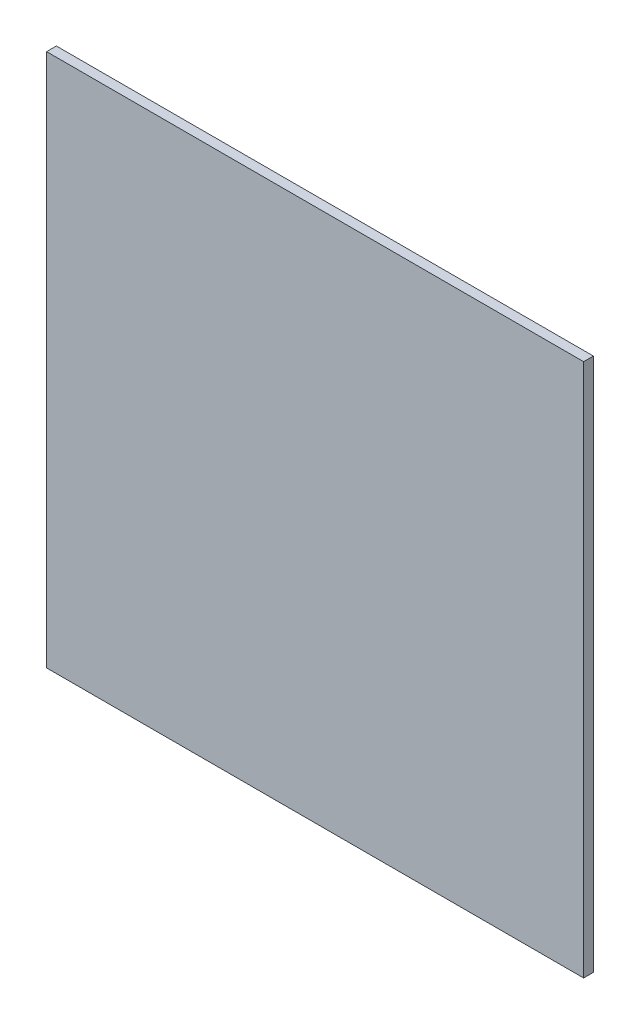
SolidWorks part; units mm, degrees
ref_plane "Plan de face" through (0, 0, 0) normal (0, 0, 1) x (1, 0, 0)
ref_plane "Plan de dessus" through (0, 0, 0) normal (0, 1, 0) x (1, 0, 0)
ref_plane "Plan de droite" through (0, 0, 0) normal (1, 0, 0) x (0, 0, -1)
sketch "Esquisse1" plane through (0, 0, 0) normal (0, 0, 1) x (1, 0, 0)
  line L1 (0, 0) -> (-330, 0)
  line L2 (0, 0) -> (0, 328)
  line L3 (0, 328) -> (-330, 328)
  line L4 (-330, 0) -> (-330, 328)
  dimension "D1" = 328
  dimension "D2" = 330
extrude "Boss.-Extru.1" add sketch "Esquisse1" along normal blind 6
